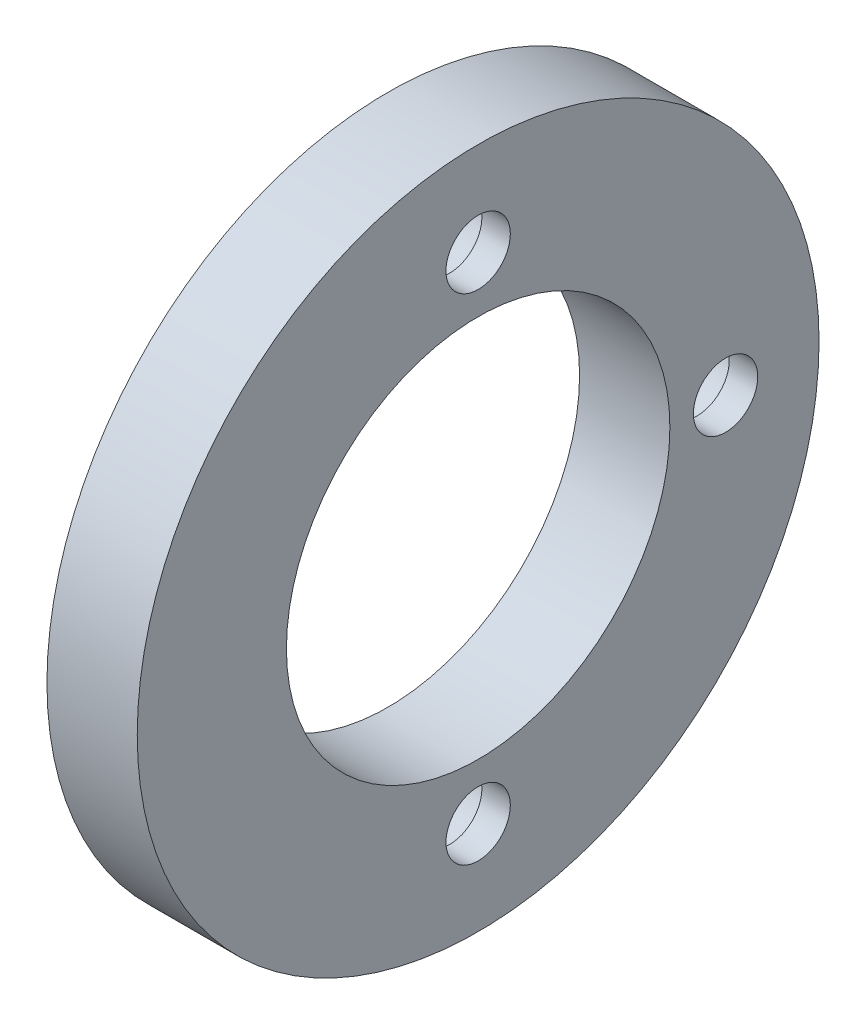
SolidWorks part; units mm, degrees
ref_plane "Front Plane" through (0, 0, 0) normal (0, 0, 1) x (1, 0, 0)
ref_plane "Top Plane" through (0, 0, 0) normal (0, 1, 0) x (1, 0, 0)
ref_plane "Right Plane" through (0, 0, 0) normal (1, 0, 0) x (0, 0, -1)
sketch "Sketch1" plane through (0, 0, 0) normal (1, 0, 0) x (0, 0, -1)
  circle A0 centre (0, 0) radius 19.685
  circle A1 centre (0, 0) radius 35
  circle A2 centre (0, 25.4) radius 3.302
  circle A3 centre (25.4, 0) radius 3.302
  circle A4 centre (0, -25.4) radius 3.302
  circle A5 centre (-25.4, 0) radius 3.302 [skipped]
  dimension "D1" = 70
  dimension "D3" = 6.604
  dimension "D5" = 39.37
  dimension "D2" = 25.4
  dimension "D4" = 4
extrude "Boss-Extrude1" add sketch "Sketch1" along normal blind 9.271
sketch "Sketch2" plane through (0, 0, 0) normal (-1, 0, 0) x (0, 0, 1)
  circle A0 centre (0, 25.4) radius 4.7625
  circle A1 centre (25.4, 0) radius 4.7625 [skipped]
  circle A2 centre (0, -25.4) radius 4.7625
  circle A3 centre (-25.4, 0) radius 4.7625
  dimension "D1" = 9.525
  dimension "D2" = 4
extrude "Cut-Extrude1" cut sketch "Sketch2" against normal blind 6.35
